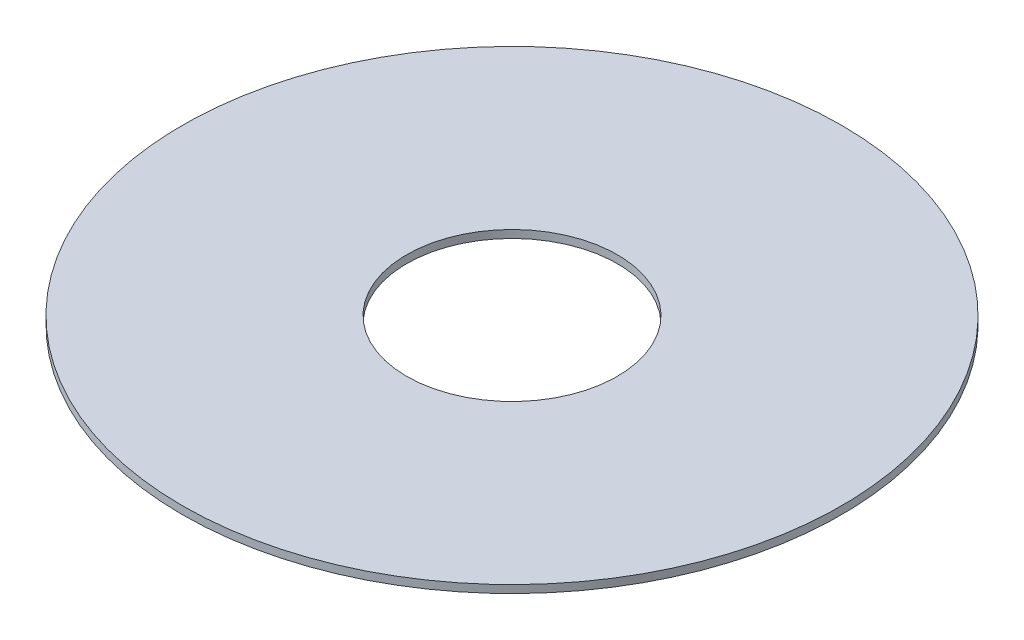
SolidWorks part; units mm, degrees
ref_plane "Front Plane" through (0, 0, 0) normal (0, 0, 1) x (1, 0, 0)
ref_plane "Top Plane" through (0, 0, 0) normal (0, 1, 0) x (1, 0, 0)
ref_plane "Right Plane" through (0, 0, 0) normal (1, 0, 0) x (0, 0, -1)
sketch "Sketch1" plane through (0, 0, 0) normal (0, 1, 0) x (1, 0, 0)
  circle A0 centre (0, 0) radius 16.92
  circle A1 centre (0, 0) radius 5.4101
  dimension "D1" = 33.84
  dimension "D2" = 10.8202
extrude "Boss-Extrude1" add sketch "Sketch1" along normal blind 0.4
equation "\"Upper_Mount_largest_radius\" =18.5"
equation "\"Lower_Mount_piston_rod_radius\"\t=4.9101"
equation "\"D1@Sketch1\"=((\"Upper_Mount_largest_radius\"*2)-1mm)*0.94"
equation "\"D2@Sketch1\"=(\"Lower_Mount_piston_rod_radius\"*2)+1mm"
equation "\"D1@Boss-Extrude1\"=\"Lower_Mount_piston_rod_radius\"/90"
equation "\"Upper_mount_wall_thickness\" =12"
equation "\"Lower_Mount_piston_rod_length\" =149"
equation "\"Piston_orifice_dia\"=0.47773"
equation "\"Spring_inner_dia\" =80"
equation "\"Spring_wire_dia\" =8"
